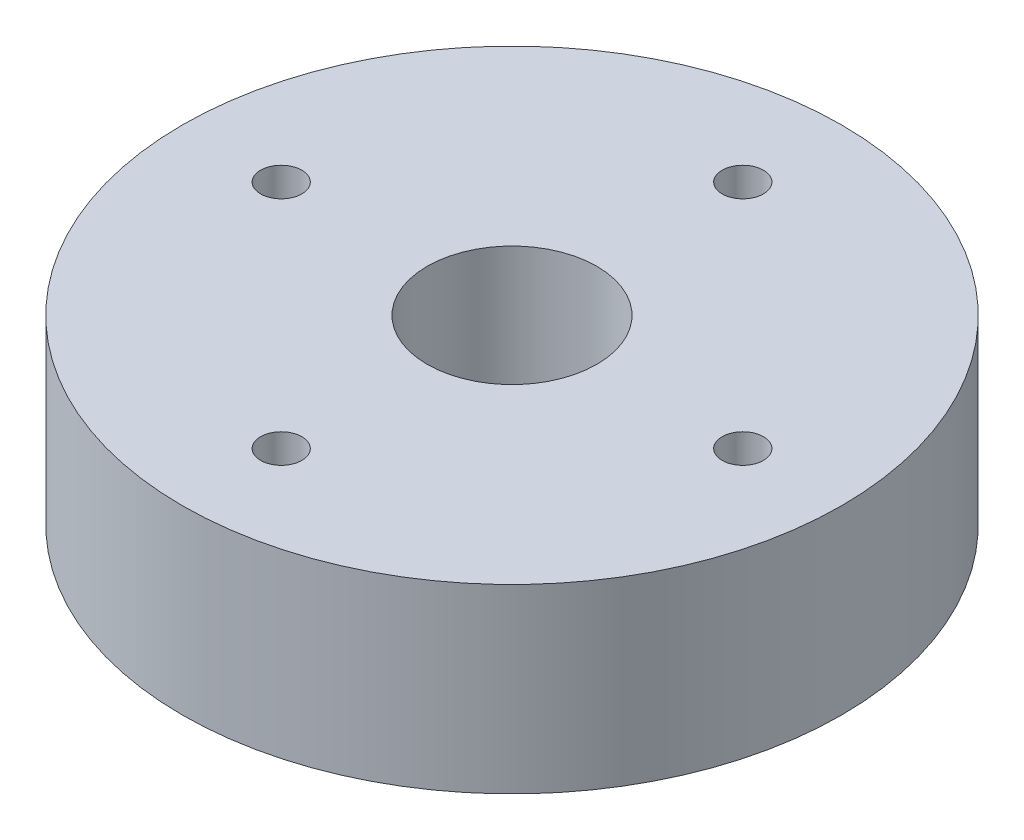
SolidWorks part; units mm, degrees
ref_plane "前视基准面" through (0, 0, 0) normal (0, 0, 1) x (1, 0, 0)
ref_plane "上视基准面" through (0, 0, 0) normal (0, 1, 0) x (1, 0, 0)
ref_plane "右视基准面" through (0, 0, 0) normal (1, 0, 0) x (0, 0, -1)
sketch "草图1" plane through (0, 0, 0) normal (0, 1, 0) x (1, 0, 0)
  circle A0 centre (0, 0) radius 20
  circle A1 centre (0, 0) radius 5.15
  dimension "D1" = 40
  dimension "D2" = 10.3
extrude "凸台-拉伸1" add sketch "草图1" along normal blind 6
sketch "草图2" plane through (0, 0, 0) normal (0, -1, 0) x (1, 0, 0)
  circle A0 centre (0, 0) radius 20
  circle A1 centre (0, 0) radius 19
  circle A2 centre (0, 0) radius 5.15
  circle A3 centre (0, 0) radius 6.5
  circle A4 centre (0, 0) radius 5.15 construction
  circle A5 centre (0, 0) radius 20 construction
  circle M4 centre (0, 0) radius 20
  circle M5 centre (0, 0) radius 5.15
  dimension "D1" = 13
  dimension "D2" = 1
extrude "凸台-拉伸2" add sketch "草图2" along normal blind 5 contours A3 M5 | A1 M4
sketch "草图3" plane through (0, -5, 0) normal (0, -1, 0) x (1, 0, 0)
  circle A2 centre (0, 0) radius 5.15 construction
  circle A3 centre (0, 0) radius 6.5
  circle A4 centre (0, 0) radius 6.5
  circle A5 centre (0, 0) radius 5.15
  dimension "D1" = 0
extrude "凸台-拉伸3" add sketch "草图3" along normal blind 7
hole_wizard "M3 螺纹孔1" positions "草图4" profile "草图5" tap size "M3" standard "GB"
sketch "草图4" plane through (0, 6, 0) normal (0, 1, 0) x (1, 0, 0)
  circle A0 centre (0, 0) radius 14 construction
  point P0 (0, 14)
  point P2 (0, -14)
  point P4 (14, 0)
  point P6 (-14, 0)
  point P13 (0, -14)
  point P14 (0, 14)
  point P15 (14, 0)
  point P16 (-14, 0)
  dimension "D1" = 28
sketch "草图5" plane through (0, 6, -14) normal (1, 0, 0) x (0, 0, 1)
  line L0 (0, 0) -> (0, 5.7511)
  line L1 (0, 5.7511) -> (1.25, 5)
  line L2 (1.25, 5) -> (1.25, 0)
  line L5 (1.25, 0) -> (0, 0)
  line L10 (0, 5.7511) -> (-1.25, 5) construction
  line L11 (0, -6.35) -> (0, 107.95) construction
  dimension "螺纹孔钻头直径" = 2.5
  dimension "螺纹孔钻头深度" = 5
  dimension "导头角度" = 118
cosmetic thread "孔螺蚊线1" parameters "D1"=6, "D2"=3
cosmetic thread "孔螺蚊线2" parameters "D1"=6, "D2"=3
cosmetic thread "孔螺蚊线3" parameters "D1"=6, "D2"=3
cosmetic thread "孔螺蚊线4" parameters "D1"=6, "D2"=3
